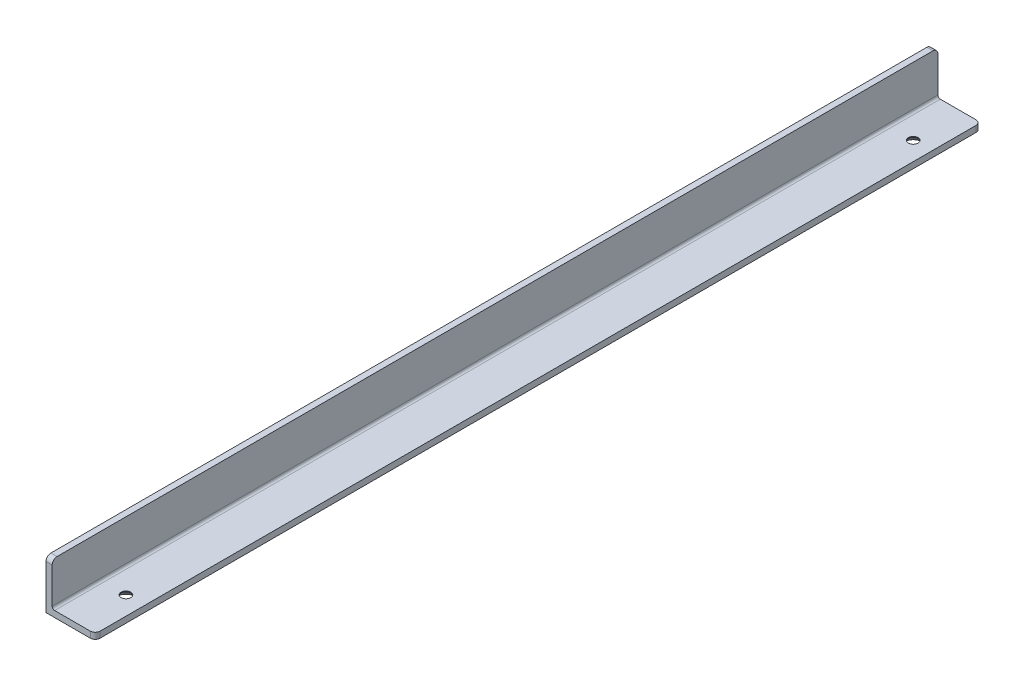
SolidWorks part; units mm, degrees
material "ASTM A36 Steel"
ref_plane "Front Plane" through (0, 0, 0) normal (0, 0, 1) x (1, 0, 0)
ref_plane "Top Plane" through (0, 0, 0) normal (0, 1, 0) x (1, 0, 0)
ref_plane "Right Plane" through (0, 0, 0) normal (1, 0, 0) x (0, 0, -1)
sketch "Sketch1" plane through (0, 0, 0) normal (0, 0, 1) x (1, 0, 0)
  line L0 (0, 0) -> (25.4, 0)
  line L2 (25.4, 3.175) -> (4.445, 3.175)
  line L3 (3.175, 4.445) -> (3.175, 25.4)
  line L6 (0, 25.4) -> (3.175, 25.4)
  line L7 (25.4, 3.175) -> (25.4, 0)
  line L8 (0, 25.4) -> (0, 0)
  arc A2 (4.445, 3.175) -> (3.175, 4.445) centre (4.445, 4.445) cw
  dimension "D3" = 3.175
  dimension "D4" = 25.4
  dimension "D5" = 1.27
  dimension "D1" = 3.175
  dimension "D2" = 25.4
extrude "Boss-Extrude1" add sketch "Sketch1" along normal mid plane 457.2
hole_wizard "CSK for #10 Flat Head Machine Screw1" positions "Sketch2" profile "Sketch3" countersink size "#10" standard "ANSI Inch" end condition up to next
sketch "Sketch2" plane through (0, 0, 0) normal (0, -1, 0) x (-1, 0, 0)
  line L1 (0, 228.6) -> (-25.4, 228.6) construction
  line L4 (0, -228.6) -> (0, 228.6) construction
  point P0 (-15.875, 203.2)
  dimension "D1" = 15.875
  dimension "D2" = 25.4
sketch "Sketch3" plane through (15.875, 0, -203.2) normal (1, 0, 0) x (0, 0, -1)
  line L0 (0, 0) -> (0, 3.175)
  line L1 (0, 3.175) -> (2.4892, 3.175)
  line L2 (2.4892, 3.175) -> (2.4892, 2.7612)
  line L3 (2.4892, 2.7612) -> (4.8895, 0)
  line L5 (4.8895, 0) -> (0, 0)
  line L6 (-2.4892, 2.7612) -> (-4.8895, 0) construction
  line L11 (0, -6.35) -> (0, 107.95) construction
  dimension "Thru Hole Dia." = 4.9784
  dimension "Thru Hole Depth" = 3.175
  dimension "Near C'Sink Dia." = 9.779
  dimension "Near C'Sink Angle" = 82
pattern_linear "LPattern2" [suppressed] count 2 spacing 76.2
mirror "Mirror1" about plane through (0, 0, 0) normal (0, 0, 1) of "CSK for #10 Flat Head Machine Screw1", "LPattern2"
fillet "Fillet1" radius 2.54 4 edges at (25.4, 1.5875, -228.6) (1.5875, 25.4, -228.6) (25.4, 1.5875, 228.6) (1.5875, 25.4, 228.6)
